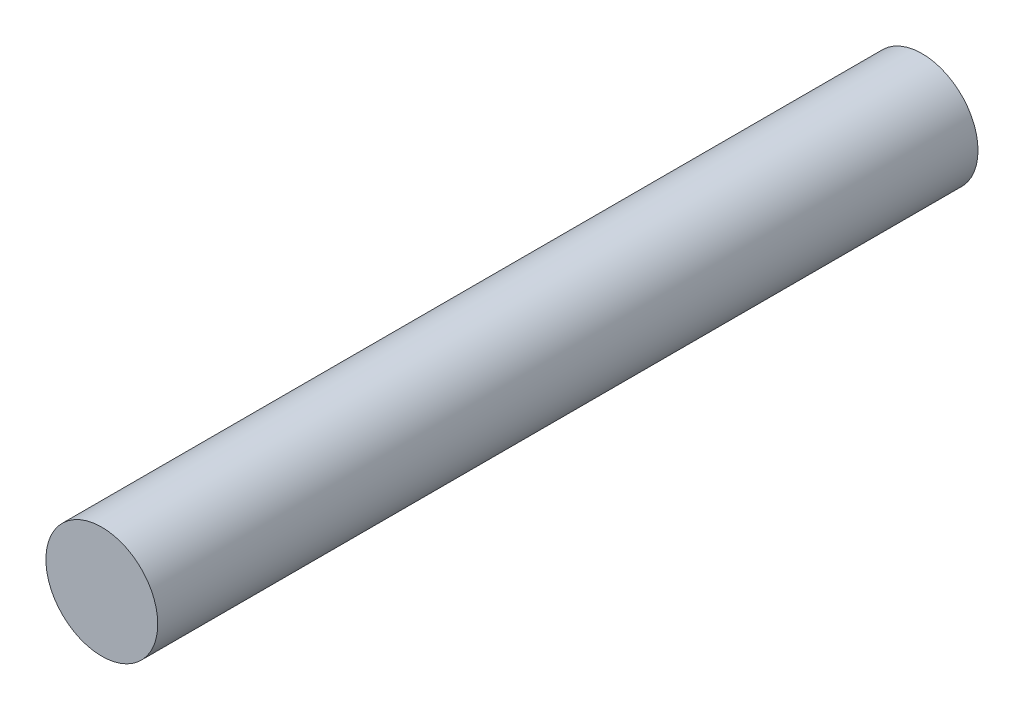
SolidWorks part; units mm, degrees
ref_plane "Front Plane" through (0, 0, 0) normal (0, 0, 1) x (1, 0, 0)
ref_plane "Top Plane" through (0, 0, 0) normal (0, 1, 0) x (1, 0, 0)
ref_plane "Right Plane" through (0, 0, 0) normal (1, 0, 0) x (0, 0, -1)
sketch "Sketch1" plane through (0, 0, 0) normal (0, 0, 1) x (1, 0, 0)
  circle A0 centre (0, 0) radius 1.5
  dimension "D1" = 3
extrude "Boss-Extrude1" add sketch "Sketch1" along normal blind 22
